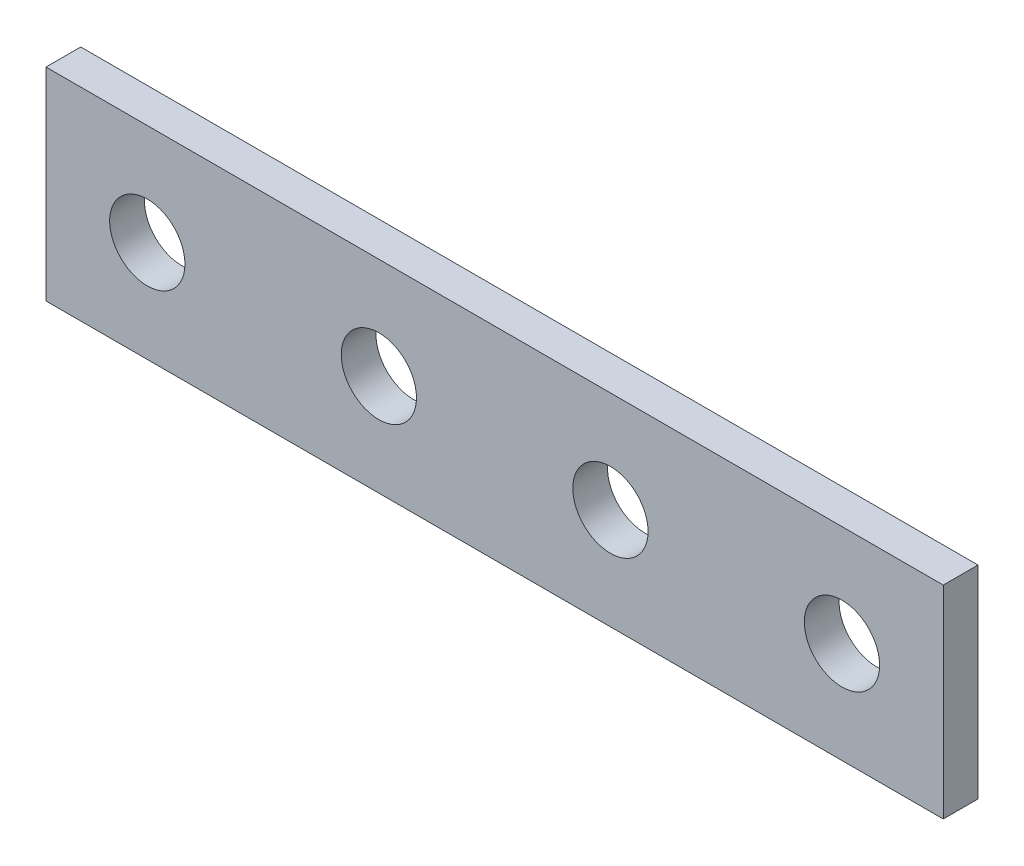
SolidWorks part; units mm, degrees
ref_plane "前视基准面" through (0, 0, 0) normal (0, 0, 1) x (1, 0, 0)
ref_plane "上视基准面" through (0, 0, 0) normal (0, 1, 0) x (1, 0, 0)
ref_plane "右视基准面" through (0, 0, 0) normal (1, 0, 0) x (0, 0, -1)
sketch "草图1" plane through (0, 0, 0) normal (0, 0, 1) x (1, 0, 0)
  line L0 (-853.9894, 35) -> (49146.0106, 35) construction
  line L1 (0, 0) -> (310, 0)
  line L2 (0, 0) -> (0, 70)
  line L3 (0, 70) -> (310, 70)
  line L4 (310, 0) -> (310, 70)
  circle A0 centre (35, 35) radius 13
  circle A1 centre (115, 35) radius 13
  circle A2 centre (195, 35) radius 13
  circle A3 centre (275, 35) radius 13
  dimension "D4" = 26
  dimension "D1" = 310
  dimension "D2" = 70
  dimension "D3" = 35
  dimension "D5" = 35
  dimension "D6" = 80
  dimension "D7" = 80
  dimension "D8" = 80
extrude "凸台-拉伸1" add sketch "草图1" along normal blind 12
